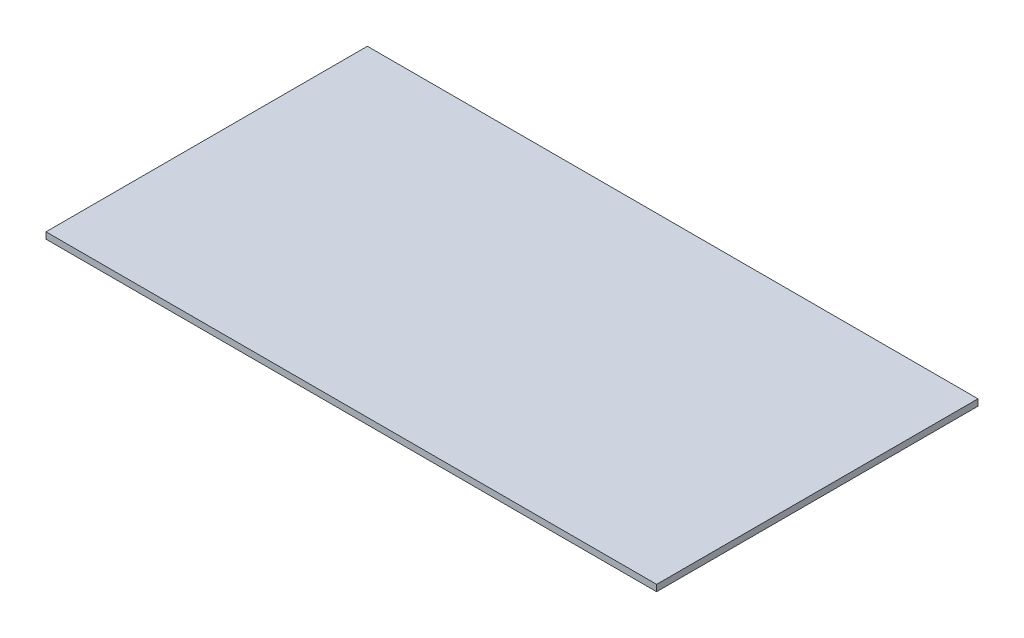
SolidWorks part; units mm, degrees
ref_plane "Front Plane" through (0, 0, 0) normal (0, 0, 1) x (1, 0, 0)
ref_plane "Top Plane" through (0, 0, 0) normal (0, 1, 0) x (1, 0, 0)
ref_plane "Right Plane" through (0, 0, 0) normal (1, 0, 0) x (0, 0, -1)
sketch "Sketch1" plane through (0, 0, 0) normal (0, 1, 0) x (1, 0, 0)
  line L1 (0, 0) -> (241.3, 0)
  line L2 (0, 0) -> (0, 127)
  line L3 (0, 127) -> (241.3, 127)
  line L4 (241.3, 0) -> (241.3, 127)
  dimension "D1" = 241.3
  dimension "D2" = 127
extrude "Boss-Extrude1" add sketch "Sketch1" along normal blind 2.54
